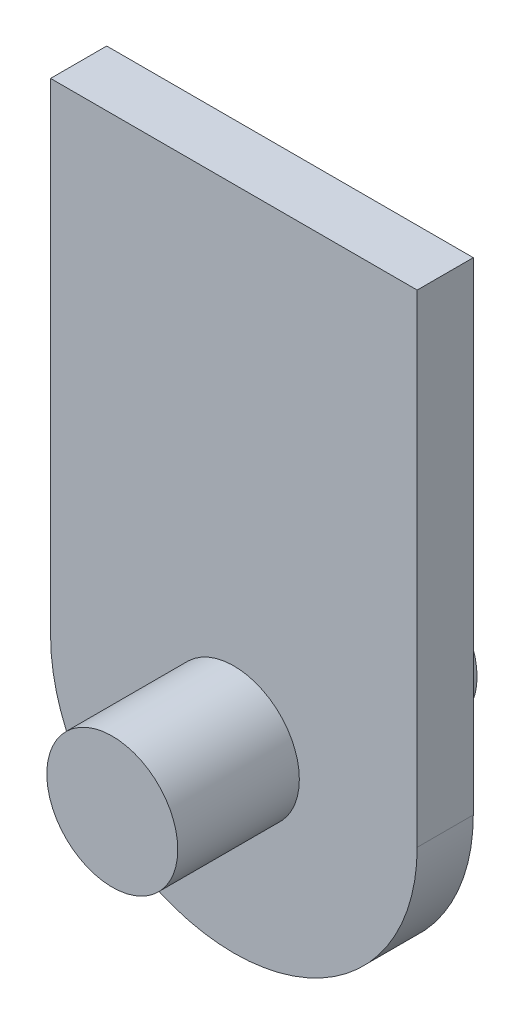
SolidWorks part; units mm, degrees
ref_plane "Front Plane" through (0, 0, 0) normal (0, 0, 1) x (1, 0, 0)
ref_plane "Top Plane" through (0, 0, 0) normal (0, 1, 0) x (1, 0, 0)
ref_plane "Right Plane" through (0, 0, 0) normal (1, 0, 0) x (0, 0, -1)
sketch "Sketch1" plane through (0, 0, 0) normal (0, 0, 1) x (1, 0, 0)
  line L0 (22.5687, 13.6635) -> (22.5687, 34.1406)
  line L1 (7.0144, 13.6635) -> (7.0144, 34.1406)
  line L2 (7.0144, 34.1406) -> (22.5687, 34.1406)
  line L3 (-6.6397, 21.4406) -> (14.7916, 21.4406) construction
  arc A0 (14.7916, 5.8863) -> (14.7916, 21.4406) centre (14.7916, 13.6635) ccw construction
  arc A1 (14.7916, 10.4885) -> (14.7916, 16.8385) centre (14.7916, 13.6635) ccw construction
  arc A2 (14.7916, 5.8863) -> (22.5687, 13.6635) centre (14.7916, 13.6635) ccw construction
  arc A3 (14.7916, 10.4885) -> (14.7916, 16.8385) centre (14.7916, 13.6635) ccw construction
  circle A4 centre (14.7916, 13.6635) radius 3.175 construction
  arc A5 (7.0144, 13.6635) -> (22.5687, 13.6635) centre (14.7916, 13.6635) ccw
  dimension "D1" = 12.7
extrude "Boss-Extrude1" add sketch "Sketch1" along normal mid plane 2.3813
sketch "Sketch2" plane through (0, 0, 0) normal (0, 0, 1) x (1, 0, 0)
  circle A0 centre (14.7916, 13.6635) radius 2.7781
  dimension "D1" = 5.5562
extrude "Boss-Extrude2" add sketch "Sketch2" along normal mid plane 12.7
